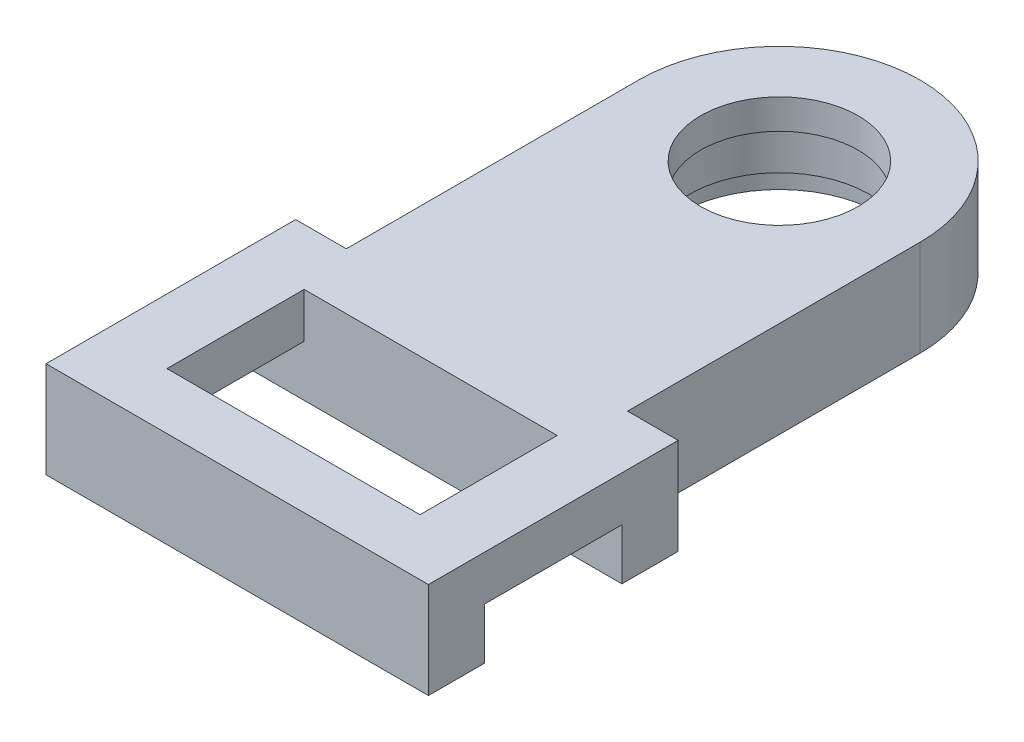
SolidWorks part; units mm, degrees
ref_plane "Front Plane" through (0, 0, 0) normal (0, 0, 1) x (1, 0, 0)
ref_plane "Top Plane" through (0, 0, 0) normal (0, 1, 0) x (1, 0, 0)
ref_plane "Right Plane" through (0, 0, 0) normal (1, 0, 0) x (0, 0, -1)
sketch "Sketch1" plane through (0, 0, 0) normal (0, 1, 0) x (1, 0, 0)
  line L1 (-11.25, -6.1) -> (11.25, -6.1)
  line L2 (-11.25, -6.1) -> (-11.25, 6.1)
  line L3 (-11.25, 6.1) -> (11.25, 6.1)
  line L4 (11.25, -6.1) -> (11.25, 6.1)
  line L5 (-11.25, -6.1) -> (11.25, 6.1) construction
  line L6 (-11.25, 6.1) -> (11.25, -6.1) construction
  line L7 (-17, -11.1) -> (17, -11.1)
  line L8 (-17, -11.1) -> (-17, 11.1)
  line L9 (-17, 11.1) -> (17, 11.1)
  line L10 (17, -11.1) -> (17, 11.1)
  line L11 (-17, -11.1) -> (17, 11.1) construction
  line L12 (-17, 11.1) -> (17, -11.1) construction
  point P0 (0, 0)
  point P6 (0, 0)
  dimension "D1" = 34
  dimension "D2" = 22.2
  dimension "D3" = 22.5
  dimension "D4" = 12.2
extrude "Boss-Extrude1" add sketch "Sketch1" along normal blind 4
sketch "Sketch2" plane through (0, 4, 0) normal (0, 1, 0) x (1, 0, 0)
  line L5 (-12.5, 37.1) -> (-12.5, 11.1)
  line L6 (17, 11.1) -> (-17, 11.1) construction
  line L7 (12.5, 37.1) -> (12.5, 11.1)
  line L8 (-12.5, 11.1) -> (12.5, 11.1)
  arc A2 (12.5, 37.1) -> (-12.5, 37.1) centre (0, 37.1) ccw
  circle A3 centre (0, 37.1) radius 8
  dimension "D3" = 16
  dimension "D1" = 12.5
  dimension "D2" = 26
extrude "Boss-Extrude3" add sketch "Sketch2" against normal through all
sketch "Sketch3" plane through (0, 0, 0) normal (0, -1, 0) x (1, 0, 0)
  circle A0 centre (0, -37.1) radius 8 construction
  circle A1 centre (0, -37.1) radius 8
  circle A3 centre (0, -37.1) radius 9
  dimension "D1" = 1
extrude "Boss-Extrude4" add sketch "Sketch3" along normal blind 2.55
sketch "Sketch4" plane through (0, 0, 0) normal (0, -1, 0) x (1, 0, 0)
  line L7 (17, -11.1) -> (17, 11.1)
  line L8 (17, 11.1) -> (-17, 11.1)
  line L9 (-17, 11.1) -> (-17, -11.1)
  line L10 (-17, -11.1) -> (-12.5, -11.1)
  line L11 (-12.5, -11.1) -> (-12.5, -37.1)
  line L12 (12.5, -37.1) -> (12.5, -11.1)
  line L13 (12.5, -11.1) -> (17, -11.1)
  line L14 (17, -11.1) -> (17, 11.1)
  line L15 (17, 11.1) -> (-17, 11.1)
  line L16 (-17, 11.1) -> (-17, -11.1)
  line L17 (-17, -11.1) -> (-12.5, -11.1)
  line L18 (-12.5, -11.1) -> (-12.5, -37.1)
  line L19 (12.5, -37.1) -> (12.5, -11.1)
  line L20 (12.5, -11.1) -> (17, -11.1)
  line L22 (-11.25, 6.1) -> (11.25, 6.1) construction
  line L23 (-11.25, 6.1) -> (11.25, 6.1)
  line L24 (11.25, -6.1) -> (-11.25, -6.1) construction
  line L25 (11.25, -6.1) -> (-11.25, -6.1)
  line L26 (-11.25, 6.1) -> (-17, 6.1)
  line L27 (11.25, 6.1) -> (17, 6.1)
  line L28 (-11.25, -6.1) -> (-17, -6.1)
  line L29 (11.25, -6.1) -> (17, -6.1)
  circle A0 centre (0, -37.1) radius 9 construction
  arc A1 (-12.5, -37.1) -> (12.5, -37.1) centre (0, -37.1) ccw
  arc A2 (-12.5, -37.1) -> (12.5, -37.1) centre (0, -37.1) ccw
  circle A3 centre (0, -37.1) radius 9
  line M9 (-11.25, 6.1) -> (11.25, 6.1)
  line M11 (11.25, -6.1) -> (-11.25, -6.1)
  line M13 (17, -11.1) -> (17, 11.1)
  line M14 (17, 11.1) -> (-17, 11.1)
  line M15 (-17, 11.1) -> (-17, -11.1)
  line M16 (-17, -11.1) -> (-12.5, -11.1)
  line M17 (-12.5, -11.1) -> (-12.5, -37.1)
  arc M18 (-12.5, -37.1) -> (12.5, -37.1) centre (0, -37.1) ccw
  line M19 (12.5, -37.1) -> (12.5, -11.1)
  line M20 (12.5, -11.1) -> (17, -11.1)
  circle M21 centre (0, -37.1) radius 9
  dimension "D1" = 0
extrude "Boss-Extrude5" add sketch "Sketch4" along normal blind 4.55 contours L29 L28 M11 M15 M16 M17 M18 M19 M20 M13 M21 | L27 L14 L26 M9 M14 M15
sketch "Sketch5" plane through (0, 4, 0) normal (0, 1, 0) x (1, 0, 0)
  circle A0 centre (0, 37.1) radius 8 construction
  circle A1 centre (0, 37.1) radius 8
  circle A2 centre (0, 37.1) radius 7
  dimension "D1" = 1
extrude "Boss-Extrude8" add sketch "Sketch5" against normal blind 2.65
